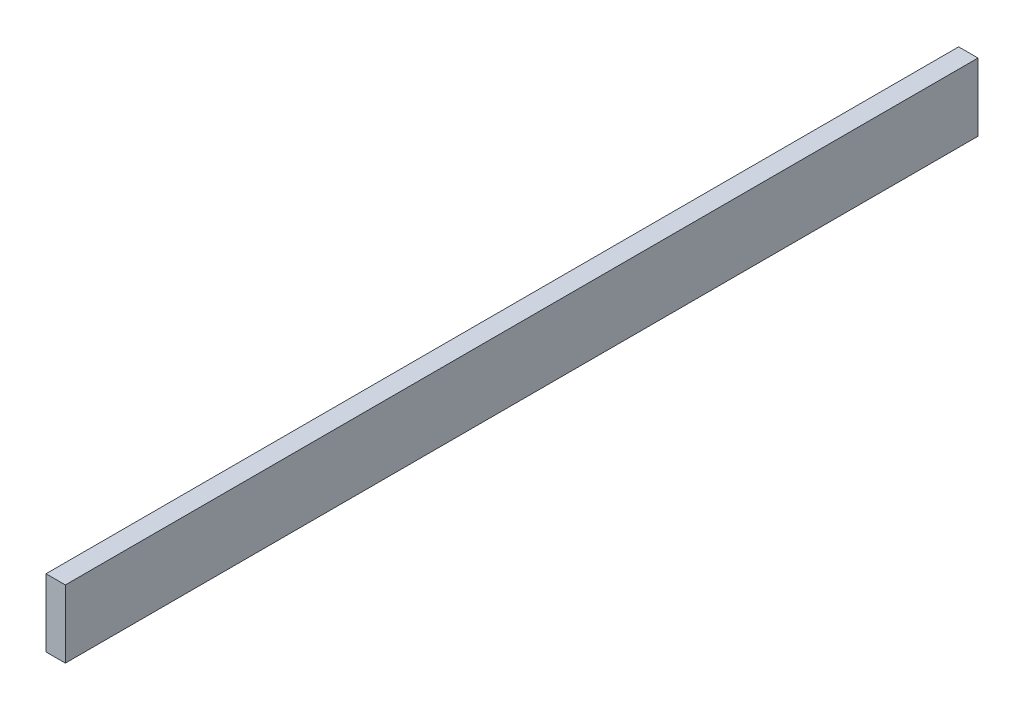
SolidWorks part; units mm, degrees
ref_plane "Front Plane" through (0, 0, 0) normal (0, 0, 1) x (1, 0, 0)
ref_plane "Top Plane" through (0, 0, 0) normal (0, 1, 0) x (1, 0, 0)
ref_plane "Right Plane" through (0, 0, 0) normal (1, 0, 0) x (0, 0, -1)
other "Configuration Table"
sketch "Sketch1" plane through (0, 0, 0) normal (0, 0, 1) x (1, 0, 0)
  line L1 (1324, 1528) -> (1338, 1528)
  line L2 (1324, 1528) -> (1324, 1577)
  line L3 (1324, 1577) -> (1338, 1577)
  line L4 (1338, 1528) -> (1338, 1577)
extrude "DET2_ray_dis_profil_sag_1" add sketch "Sketch1" against normal blind 660 separate body
